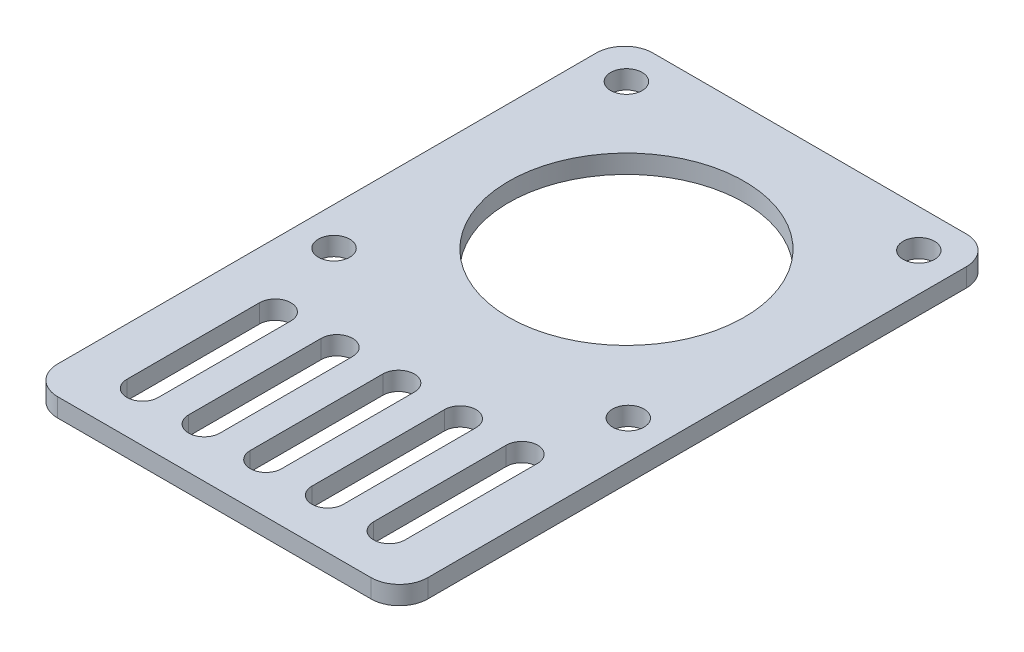
SolidWorks part; units mm, degrees
ref_plane "Спереди" through (0, 0, 0) normal (0, 0, 1) x (1, 0, 0)
ref_plane "Сверху" through (0, 0, 0) normal (0, 1, 0) x (1, 0, 0)
ref_plane "Справа" through (0, 0, 0) normal (1, 0, 0) x (0, 0, -1)
sketch "Эскиз1" plane through (0, 0, 0) normal (0, 1, 0) x (1, 0, 0)
  line L0 (30, 0) -> (30, -103.5264) construction
  line L1 (4.6, 0) -> (55.4, 0)
  line L2 (0, -4.6) -> (0, -91.9)
  line L3 (4.6, -96.5) -> (55.4, -96.5)
  line L4 (60, -4.6) -> (60, -91.9)
  line L5 (10.3114, -66.95) -> (10.3114, -88.45) construction
  line L6 (12.8614, -66.95) -> (12.8614, -88.45)
  line L7 (7.7614, -66.95) -> (7.7614, -88.45)
  line L8 (20.3114, -66.95) -> (20.3114, -88.45) construction
  line L9 (22.8614, -66.95) -> (22.8614, -88.45)
  line L10 (17.7614, -66.95) -> (17.7614, -88.45)
  line L11 (30.3114, -66.95) -> (30.3114, -88.45) construction
  line L12 (32.8614, -66.95) -> (32.8614, -88.45)
  line L13 (27.7614, -66.95) -> (27.7614, -88.45)
  line L14 (40.3114, -66.95) -> (40.3114, -88.45) construction
  line L15 (42.8614, -66.95) -> (42.8614, -88.45)
  line L16 (37.7614, -66.95) -> (37.7614, -88.45)
  line L17 (50.3114, -66.95) -> (50.3114, -88.45) construction
  line L18 (52.8614, -66.95) -> (52.8614, -88.45)
  line L19 (47.7614, -66.95) -> (47.7614, -88.45)
  circle A0 centre (6.45, -6.15) radius 2.55
  circle A1 centre (53.85, -6.15) radius 2.55
  circle A2 centre (6.15, -53.25) radius 2.55
  circle A3 centre (53.85, -53.25) radius 2.55
  circle A4 centre (30, -29.7) radius 19.1
  arc A5 (12.8614, -66.95) -> (7.7614, -66.95) centre (10.3114, -66.95) ccw
  arc A6 (7.7614, -88.45) -> (12.8614, -88.45) centre (10.3114, -88.45) ccw
  arc A7 (22.8614, -66.95) -> (17.7614, -66.95) centre (20.3114, -66.95) ccw
  arc A8 (17.7614, -88.45) -> (22.8614, -88.45) centre (20.3114, -88.45) ccw
  arc A9 (32.8614, -66.95) -> (27.7614, -66.95) centre (30.3114, -66.95) ccw
  arc A10 (27.7614, -88.45) -> (32.8614, -88.45) centre (30.3114, -88.45) ccw
  arc A11 (42.8614, -66.95) -> (37.7614, -66.95) centre (40.3114, -66.95) ccw
  arc A12 (37.7614, -88.45) -> (42.8614, -88.45) centre (40.3114, -88.45) ccw
  arc A13 (52.8614, -66.95) -> (47.7614, -66.95) centre (50.3114, -66.95) ccw
  arc A14 (47.7614, -88.45) -> (52.8614, -88.45) centre (50.3114, -88.45) ccw
  arc A15 (4.6, 0) -> (0, -4.6) centre (4.6, -4.6) ccw
  arc A16 (55.4, 0) -> (60, -4.6) centre (55.4, -4.6) cw
  arc A17 (55.4, -96.5) -> (60, -91.9) centre (55.4, -91.9) ccw
  arc A18 (0, -91.9) -> (4.6, -96.5) centre (4.6, -91.9) ccw
  point P19 (10.3114, -77.7)
  point P27 (20.3114, -77.7)
  point P34 (30.3114, -77.7)
  point P41 (40.3114, -77.7)
  point P48 (50.3114, -77.7)
  point P54 (0, 0)
  point P57 (60, 0)
  point P62 (0, -96.5)
  dimension "D3" = 5.1
  dimension "D4" = 5.1
  dimension "D5" = 5.1
  dimension "D6" = 5.1
  dimension "D8" = 6.15
  dimension "D9" = 6.15
  dimension "D10" = 38.2
  dimension "D11" = 29.7
  dimension "D12" = 47.1
  dimension "D13" = 6.15
  dimension "D14" = 6.15
  dimension "D15" = 6.15
  dimension "D16" = 47.1
  dimension "D17" = 66.95
  dimension "D18" = 5
  dimension "D19" = 4.6
  dimension "D1" = 60
  dimension "D2" = 96.5
  dimension "D7" = 6.45
extrude "Бобышка-Вытянуть1" add sketch "Эскиз1" along normal blind 3
